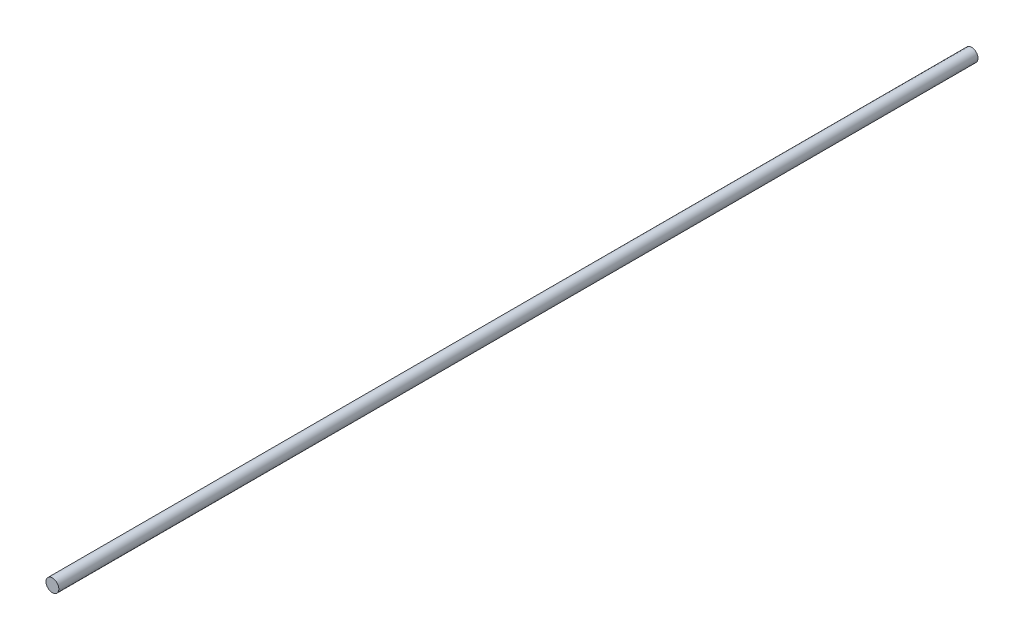
SolidWorks part; units mm, degrees
ref_plane "Płaszczyzna przednia" through (0, 0, 0) normal (0, 0, 1) x (1, 0, 0)
ref_plane "Płaszczyzna górna" through (0, 0, 0) normal (0, 1, 0) x (1, 0, 0)
ref_plane "Płaszczyzna prawa" through (0, 0, 0) normal (1, 0, 0) x (0, 0, -1)
sketch "Sketch1" plane through (0, 0, 0) normal (0, 0, 1) x (1, 0, 0)
  circle A0 centre (-2.9929, 0.0519) radius 1.5
  dimension "D1" = 3
extrude "Boss-Extrude2" add sketch "Sketch1" along normal blind 215
